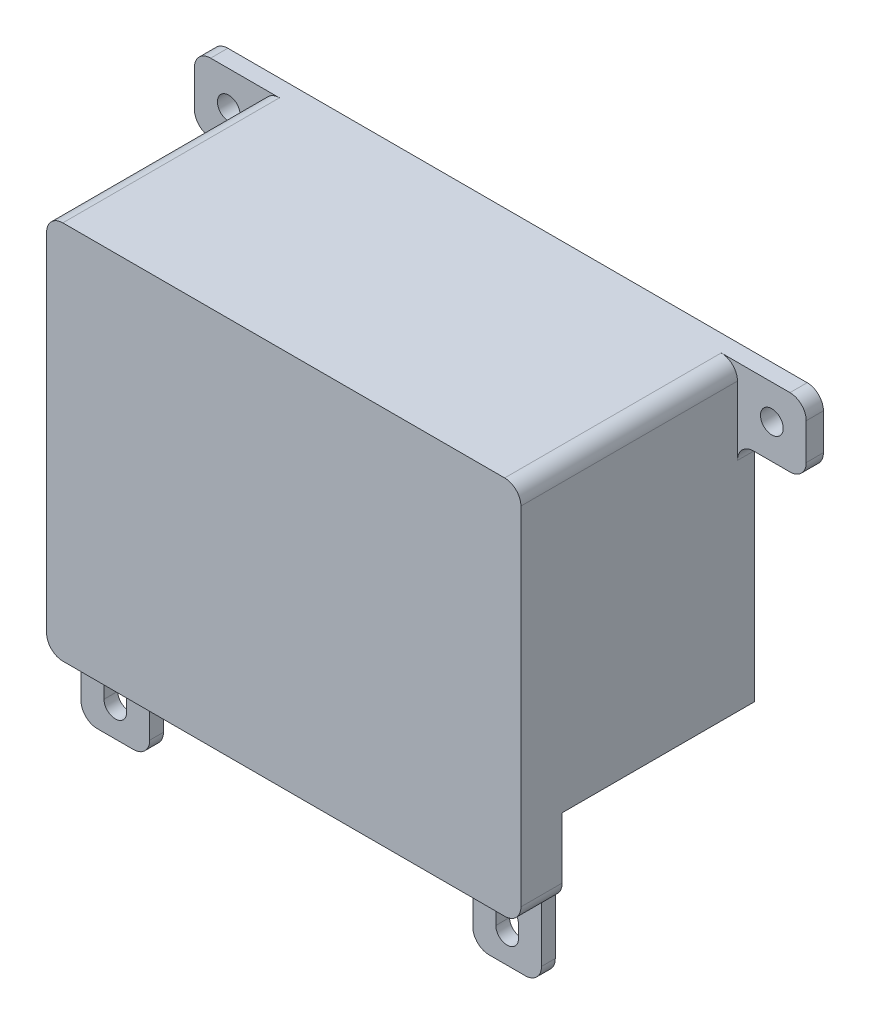
SolidWorks part; units mm, degrees
material "ABS"
ref_plane "X-Y Datum" through (0, 0, 0) normal (0, 0, 1) x (1, 0, 0)
ref_plane "X-Z Datum" through (0, 0, 0) normal (0, 1, 0) x (1, 0, 0)
ref_plane "Y-Z Datum" through (0, 0, 0) normal (1, 0, 0) x (0, 0, -1)
sketch "Sketch1" plane through (0, 0, 0) normal (0, 0, 1) x (1, 0, 0)
  line L0 (6.33, 73.27) -> (88.87, 73.27)
  line L1 (7.6, 72) -> (87.6, 72) construction
  line L2 (7.6, 72) -> (7.6, 9.5) construction
  line L3 (7.6, 9.5) -> (87.6, 9.5) construction
  line L4 (87.6, 72) -> (87.6, 9.5) construction
  line L5 (88.87, 73.27) -> (88.87, 8.23)
  line L6 (6.33, 8.23) -> (88.87, 8.23)
  line L7 (6.33, 73.27) -> (6.33, 8.23)
  circle A0 centre (12.6, 67) radius 2.125 construction
  circle A1 centre (82.6, 67) radius 2.125 construction
  circle A2 centre (82.6, 17) radius 2.125 construction
  circle A3 centre (12.6, 17) radius 2.125 construction
  dimension "D1" = 1.27
extrude "Boss-Extrude1" add sketch "Sketch1" along normal blind 43.18
shell "Shell1" thickness 2.54
sketch "Sketch6" plane through (3.79, 0, 0) normal (-1, 0, 0) x (0, 0, 1)
  line L24 (0, 81.9051) -> (38.1, 81.9051) construction
  line L25 (2.54, 59.03) -> (2.54, 73.27)
  line L26 (0, 59.03) -> (0, 3.15)
  line L27 (38.1, 3.15) -> (0, 3.15)
  line L28 (38.1, 19.9292) -> (38.1, 3.15)
  line L30 (2.54, 73.27) -> (0, 73.27)
  line L31 (0, 73.27) -> (0, 59.03)
  line L32 (20.32, 59.03) -> (20.32, 19.9292) construction
  line L34 (2.54, 19.9292) -> (38.1, 19.9292)
  line L35 (2.54, 59.03) -> (2.54, 19.9292)
  point P0 (0, 73.27)
extrude "Cut-Extrude2" cut sketch "Sketch6" against normal through all
sketch "Sketch7" plane through (0, 73.27, 0) normal (0, 1, 0) x (1, 0, 0)
  line L1 (3.79, -45.72) -> (91.41, -45.72)
  line L2 (3.79, -45.72) -> (3.79, -2.54)
  line L3 (3.79, -2.54) -> (91.41, -2.54)
  line L4 (91.41, -45.72) -> (91.41, -2.54)
extrude "Boss-Extrude2" add sketch "Sketch7" along normal blind 2.54
sketch "Sketch8" plane through (0, 0, 2.54) normal (0, 0, -1) x (-1, 0, 0)
  line L0 (-65.4056, 75.81) -> (-65.4056, 73.27)
  line L3 (-88.87, 73.27) -> (-6.33, 73.27) construction
  line L4 (-90.14, 19.9292) -> (-90.14, 74.54)
  line L5 (-91.41, 19.9292) -> (-88.87, 19.9292) construction
  line L6 (-5.06, 19.9292) -> (-5.06, 74.54)
  line L7 (-6.33, 19.9292) -> (-3.79, 19.9292) construction
  line L8 (-5.06, 74.54) -> (-90.14, 74.54)
  line L9 (-90.14, 19.9292) -> (-88.87, 19.9292)
  line L10 (-88.87, 19.9292) -> (-88.87, 73.27)
  line L11 (-88.87, 73.27) -> (-6.33, 73.27)
  line L12 (-6.33, 73.27) -> (-6.33, 19.9292)
  line L13 (-6.33, 19.9292) -> (-3.79, 19.9292) construction
  line L14 (-6.33, 19.9292) -> (-5.06, 19.9292)
  line M2 (-6.33, 73.27) -> (-6.33, 19.9292)
  line M3 (-6.33, 19.9292) -> (-3.79, 19.9292)
  line M7 (-91.41, 19.9292) -> (-88.87, 19.9292)
  line M8 (-88.87, 19.9292) -> (-88.87, 73.27)
  line M9 (-88.87, 73.27) -> (-6.33, 73.27)
extrude "Cut-Extrude3" cut sketch "Sketch8" against normal blind 2.54 contours L0 L8 L4 M7 M8 M9 | L6 L8 L0 M9 M2 M3
sketch "Sketch9" plane through (0, 0, 38.1) normal (0, 0, -1) x (-1, 0, 0)
  line L3 (-90.14, 19.9292) -> (-90.14, 6.96)
  line L4 (-90.14, 6.96) -> (-5.06, 6.96)
  line L5 (-5.06, 6.96) -> (-5.06, 19.9292)
  line L6 (-6.33, 19.9292) -> (-3.79, 19.9292) construction
  line L7 (-5.06, 19.9292) -> (-6.33, 19.9292)
  line L8 (-6.33, 19.9292) -> (-6.33, 8.23)
  line L9 (-6.33, 8.23) -> (-88.87, 8.23)
  line L10 (-88.87, 8.23) -> (-88.87, 19.9292)
  line L11 (-88.87, 19.9292) -> (-90.14, 19.9292)
extrude "Cut-Extrude4" cut sketch "Sketch9" against normal blind 2.54
sketch "Sketch10" plane through (0, 19.9292, 0) normal (0, -1, 0) x (1, 0, 0)
  line L1 (5.06, 5.08) -> (6.33, 5.08)
  line L2 (5.06, 5.08) -> (5.06, 40.64)
  line L3 (5.06, 40.64) -> (6.33, 40.64)
  line L4 (6.33, 5.08) -> (6.33, 40.64)
  line L5 (90.14, 5.08) -> (88.87, 5.08)
  line L6 (90.14, 5.08) -> (90.14, 40.64)
  line L7 (90.14, 40.64) -> (88.87, 40.64)
  line L8 (88.87, 5.08) -> (88.87, 40.64)
extrude "Cut-Extrude5" cut sketch "Sketch10" against normal blind 2.54
sketch "Sketch11" plane through (0, 5.69, 0) normal (0, -1, 0) x (1, 0, 0)
  line L0 (90.14, 5.08) -> (90.14, 40.64) construction
  line L1 (5.06, 38.1) -> (17.76, 38.1)
  line L2 (5.06, 38.1) -> (5.06, 40.64)
  line L3 (5.06, 40.64) -> (17.76, 40.64)
  line L4 (17.76, 38.1) -> (17.76, 40.64)
  line L5 (90.14, 38.1) -> (77.44, 38.1)
  line L6 (90.14, 38.1) -> (90.14, 40.64)
  line L7 (90.14, 40.64) -> (77.44, 40.64)
  line L8 (77.44, 38.1) -> (77.44, 40.64)
  line L9 (91.41, 38.1) -> (90.14, 38.1) construction
extrude "Boss-Extrude3" add sketch "Sketch11" along normal blind 12.7
sketch "Sketch12" plane through (0, 0, 40.64) normal (0, 0, 1) x (1, 0, 0)
  line L0 (11.41, -0.6201) -> (11.41, 0.61) construction
  line L3 (11.41, -0.6201) -> (11.41, -1.6835) construction
  line L4 (9.31, 0.61) -> (9.31, -1.6835)
  line L5 (13.51, 0.61) -> (13.51, -1.6835)
  line L6 (47.6, 5.69) -> (47.6, 25.4131) construction
  line L7 (3.79, 5.69) -> (91.41, 5.69) construction
  line L8 (83.79, -0.6201) -> (83.79, -1.6835) construction
  line L9 (83.79, -0.6201) -> (83.79, 0.61) construction
  line L10 (81.69, 0.61) -> (81.69, -1.6835)
  line L11 (85.89, 0.61) -> (85.89, -1.6835)
  arc A0 (13.51, 0.61) -> (9.31, 0.61) centre (11.41, 0.61) ccw
  arc A1 (9.31, -1.6835) -> (13.51, -1.6835) centre (11.41, -1.6835) ccw
  arc A2 (85.89, -1.6835) -> (81.69, -1.6835) centre (83.79, -1.6835) cw
  arc A3 (81.69, 0.61) -> (85.89, 0.61) centre (83.79, 0.61) cw
  point P6 (11.41, -0.6201)
  point P19 (83.79, -0.6201)
ref_plane "Plane1" through (47.6, 0, 0) normal (-1, 0, 0) x (0, 0, 1)
extrude "Cut-Extrude7" cut sketch "Sketch12" against normal through all
sketch "Sketch13" plane through (0, 0, 2.54) normal (0, 0, -1) x (-1, 0, 0)
  line L1 (-91.41, 75.81) -> (-104.11, 75.81)
  line L2 (-91.41, 75.81) -> (-91.41, 63.11)
  line L3 (-91.41, 63.11) -> (-104.11, 63.11)
  line L4 (-104.11, 75.81) -> (-104.11, 63.11)
  line L5 (-3.79, 75.81) -> (8.91, 75.81)
  line L6 (-3.79, 75.81) -> (-3.79, 63.11)
  line L7 (-3.79, 63.11) -> (8.91, 63.11)
  line L8 (8.91, 75.81) -> (8.91, 63.11)
  circle A0 centre (-97.76, 69.46) radius 2.1
  circle A1 centre (2.56, 69.46) radius 2.1
extrude "Boss-Extrude4" add sketch "Sketch13" against normal blind 3.175
fillet "Fillet2" radius 3 18 edges at (5.06, 5.69, 39.37) (17.76, 5.69, 39.37) (5.06, -7.01, 39.37) (17.76, -7.01, 39.37) (90.14, 5.69, 39.37) (77.44, 5.69, 39.37) (90.14, -7.01, 39.37) (77.44, -7.01, 39.37) (91.41, 63.11, 4.1275) (104.11, 63.11, 4.1275) (104.11, 75.81, 4.1275) (3.79, 75.81, 25.7175) (3.79, 63.11, 4.1275) (-8.91, 75.81, 4.1275) (-8.91, 63.11, 4.1275) (91.41, 75.81, 25.7175) (91.41, 5.69, 41.91) (3.79, 5.69, 41.91)
